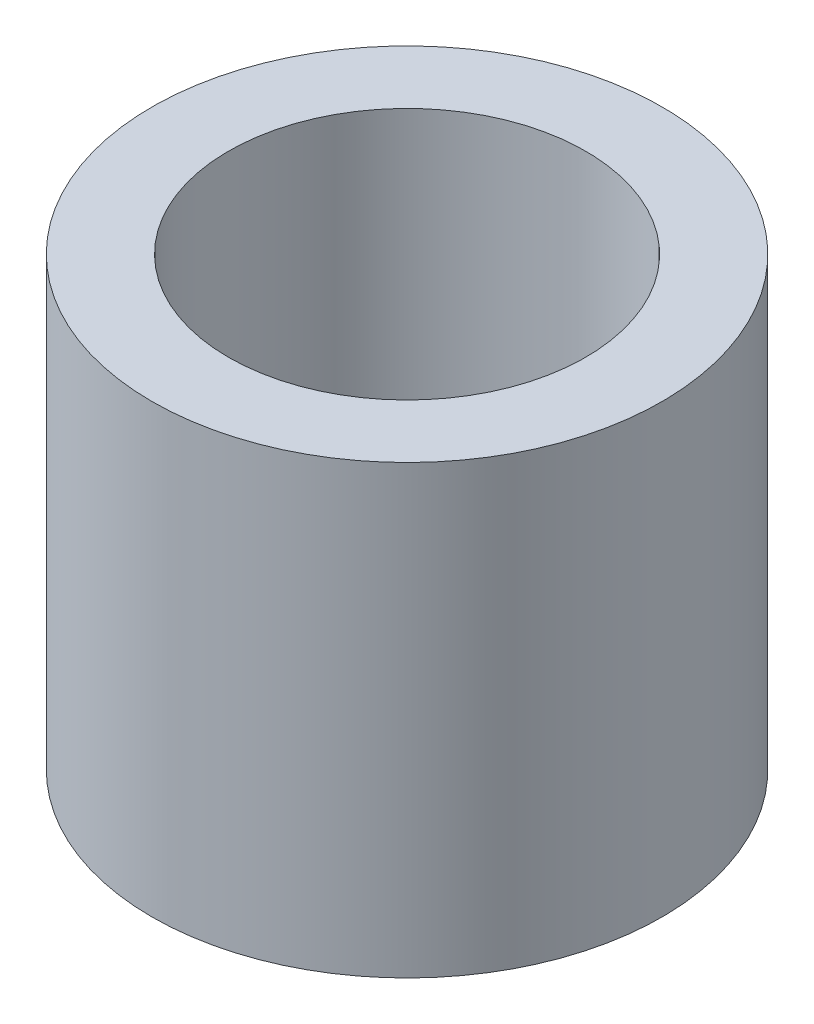
SolidWorks part; units mm, degrees
ref_plane "Front Plane" through (0, 0, 0) normal (0, 0, 1) x (1, 0, 0)
ref_plane "Top Plane" through (0, 0, 0) normal (0, 1, 0) x (1, 0, 0)
ref_plane "Right Plane" through (0, 0, 0) normal (1, 0, 0) x (0, 0, -1)
sketch "Sketch1" plane through (0, 0, 0) normal (0, 1, 0) x (1, 0, 0)
  circle A0 centre (0, 0) radius 6.35
  circle A1 centre (0, 0) radius 4.445
  dimension "D1" = 12.7
  dimension "D2" = 8.89
extrude "Boss-Extrude1" add sketch "Sketch1" along normal mid plane 11.1125
